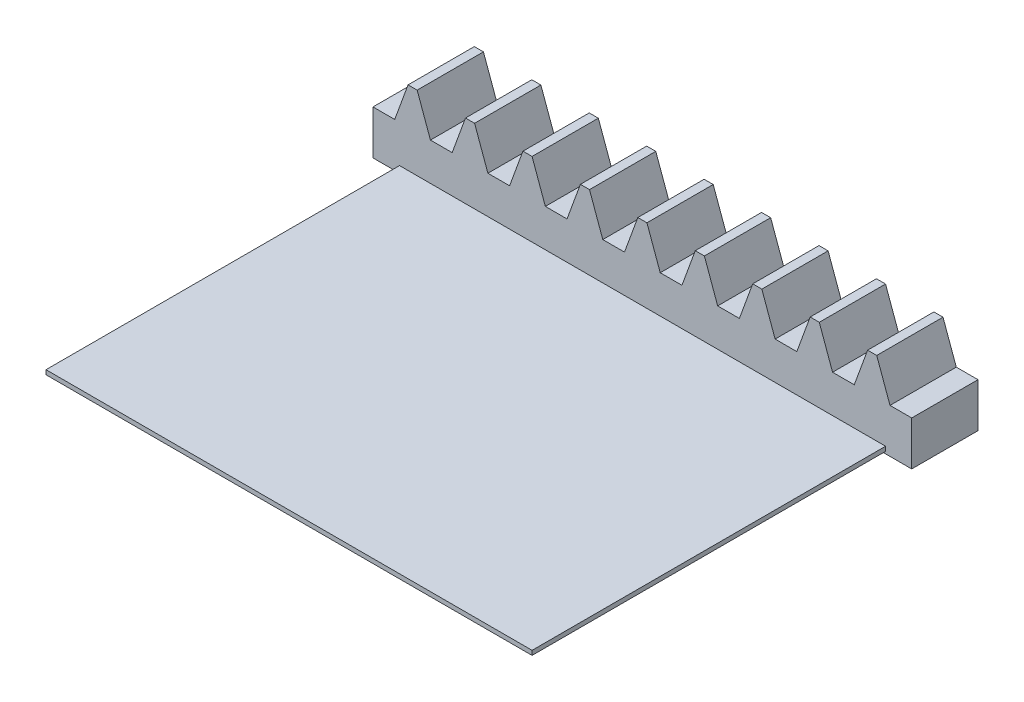
SolidWorks part; units mm, degrees
ref_plane "Front Plane" through (0, 0, 0) normal (0, 0, 1) x (1, 0, 0)
ref_plane "Top Plane" through (0, 0, 0) normal (0, 1, 0) x (1, 0, 0)
ref_plane "Right Plane" through (0, 0, 0) normal (1, 0, 0) x (0, 0, -1)
sketch "Sketch1" plane through (0, 0, 0) normal (0, 0, 1) x (1, 0, 0)
  line L0 (0, 0) -> (120, 0) construction
  line L1 (0, 0) -> (4.9133, 0)
  line L2 (0, 0) -> (0, -10)
  line L3 (2.4566, 0) -> (2.4566, 6.9552) construction
  line L4 (4.9133, 0) -> (7.9306, 8.2899)
  line L5 (17.9133, 0) -> (20.9306, 8.2899)
  line L6 (13, 0) -> (17.9133, 0)
  line L7 (13, 0) -> (9.9929, 8.2899)
  line L8 (30.9133, 0) -> (33.9306, 8.2899)
  line L9 (26, 0) -> (30.9133, 0)
  line L10 (26, 0) -> (22.9929, 8.2899)
  line L11 (43.9133, 0) -> (46.9306, 8.2899)
  line L12 (39, 0) -> (43.9133, 0)
  line L13 (39, 0) -> (35.9929, 8.2899)
  line L14 (56.9133, 0) -> (59.9306, 8.2899)
  line L15 (52, 0) -> (56.9133, 0)
  line L16 (52, 0) -> (48.9929, 8.2899)
  line L17 (69.9133, 0) -> (72.9306, 8.2899)
  line L18 (65, 0) -> (69.9133, 0)
  line L19 (65, 0) -> (61.9929, 8.2899)
  line L20 (82.9133, 0) -> (85.9306, 8.2899)
  line L21 (78, 0) -> (82.9133, 0)
  line L22 (78, 0) -> (74.9929, 8.2899)
  line L23 (95.9133, 0) -> (98.9306, 8.2899)
  line L24 (91, 0) -> (95.9133, 0)
  line L25 (91, 0) -> (87.9929, 8.2899)
  line L26 (108.9133, 0) -> (111.9306, 8.2899)
  line L27 (104, 0) -> (108.9133, 0)
  line L28 (104, 0) -> (100.9929, 8.2899)
  line L29 (0, -10) -> (121.9133, -10)
  line L30 (117, 0) -> (121.9133, 0)
  line L31 (117, 0) -> (113.9929, 8.2899)
  line L32 (7.9306, 8.2899) -> (9.9929, 8.2899)
  line L33 (20.9306, 8.2899) -> (22.9929, 8.2899)
  line L34 (33.9306, 8.2899) -> (35.9929, 8.2899)
  line L35 (46.9306, 8.2899) -> (48.9929, 8.2899)
  line L36 (59.9306, 8.2899) -> (61.9929, 8.2899)
  line L37 (72.9306, 8.2899) -> (74.9929, 8.2899)
  line L38 (85.9306, 8.2899) -> (87.9929, 8.2899)
  line L39 (98.9306, 8.2899) -> (100.9929, 8.2899)
  line L40 (111.9306, 8.2899) -> (113.9929, 8.2899)
  line L41 (121.9133, 0) -> (124.9306, 8.2899) [skipped]
  line L42 (121.9133, -10) -> (121.9133, 0)
  dimension "D1" = 120
  dimension "D2" = 4.9133
  dimension "D4" = 10
extrude "Boss-Extrude1" add sketch "Sketch1" along normal blind 15
sketch "Sketch2" plane through (0, 0, 15) normal (0, 0, 1) x (1, 0, 0)
  line L1 (6, -8.5) -> (116, -8.5)
  line L3 (0, -10) -> (121.9133, -10) construction
  line L4 (6, -9.5) -> (116, -9.5)
  line L5 (6, -8.5) -> (6, -9.5)
  line L6 (116, -8.5) -> (116, -9.5)
  dimension "D1" = 1.5
  dimension "D2" = 1
sketch "Sketch7" plane through (0, 0, 15) normal (0, 0, 1) x (1, 0, 0)
extrude "Boss-Extrude3" add sketch "Sketch2" along normal blind 80
